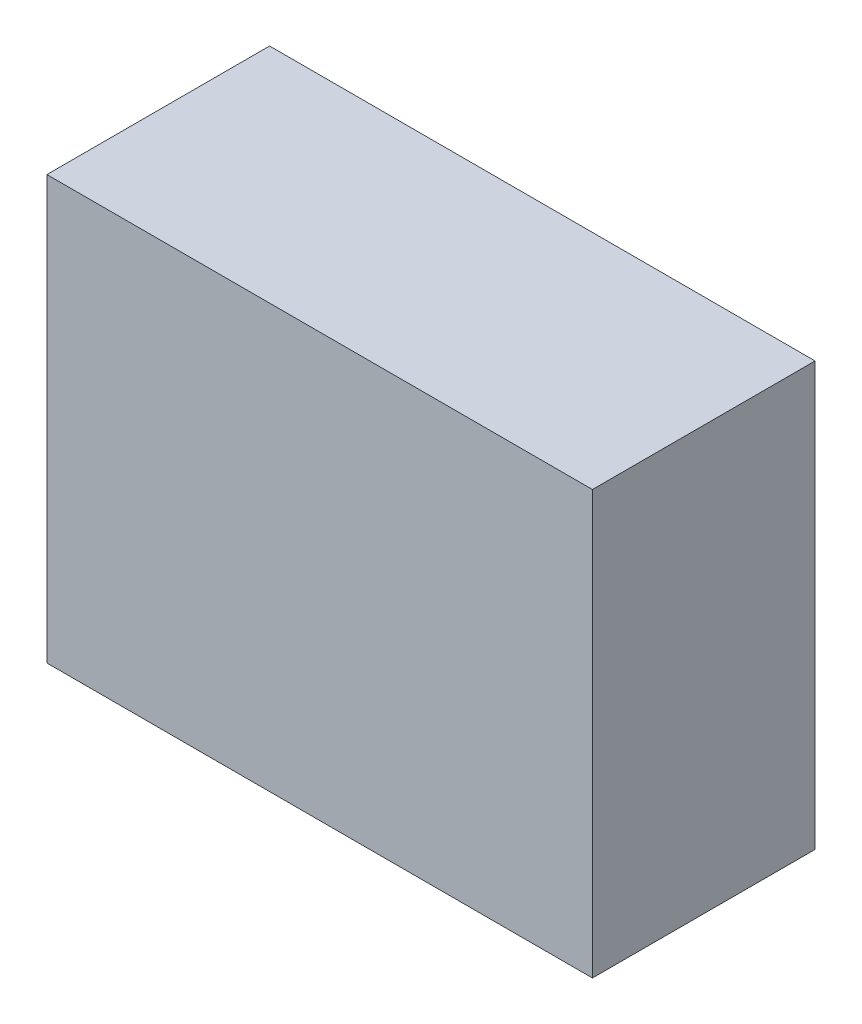
SolidWorks part; units mm, degrees
ref_plane "Front Plane" through (0, 0, 0) normal (1, 0, 0) x (0, 1, 0)
ref_plane "Top Plane" through (0, 0, 0) normal (0, 0, 1) x (0, 1, 0)
ref_plane "Right Plane" through (0, 0, 0) normal (0, 1, 0) x (-1, 0, 0)
sketch "Sketch1" plane through (0, 0, 0) normal (0, 0, 1) x (0, 1, 0)
  line L1 (-38, 49) -> (38, 49)
  line L2 (-38, 49) -> (-38, -49)
  line L3 (-38, -49) -> (38, -49)
  line L4 (38, 49) -> (38, -49)
  line L5 (-38, 49) -> (38, -49) construction
  line L6 (-38, -49) -> (38, 49) construction
  point P0 (0, 0)
  dimension "D1" = 98
  dimension "D2" = 76
extrude "Boss-Extrude1" add sketch "Sketch1" along normal blind 40
